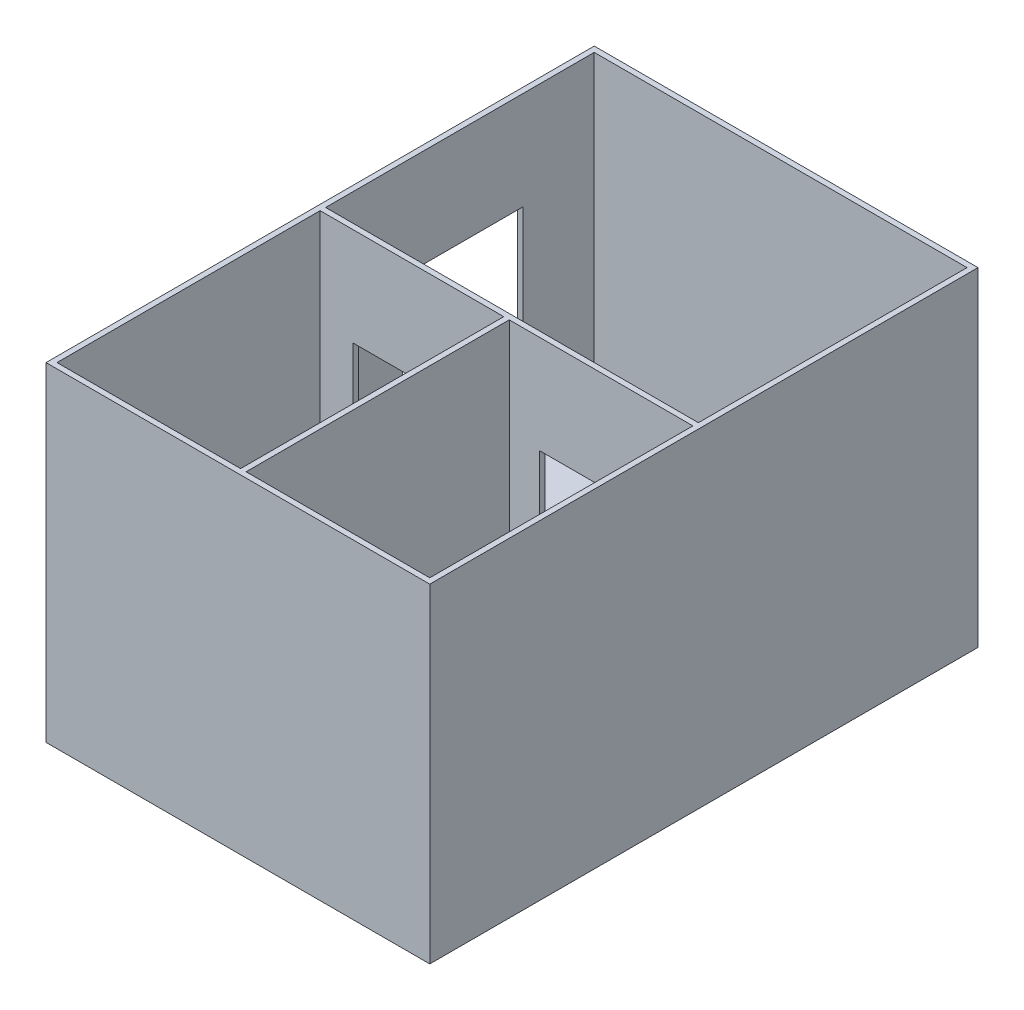
SolidWorks part; units mm, degrees
ref_plane "Front Plane" through (0, 0, 0) normal (0, 0, 1) x (1, 0, 0)
ref_plane "Top Plane" through (0, 0, 0) normal (0, 1, 0) x (1, 0, 0)
ref_plane "Right Plane" through (0, 0, 0) normal (1, 0, 0) x (0, 0, -1)
sketch "Sketch2" plane through (0, 0, 0) normal (0, 1, 0) x (1, 0, 0)
  line L1 (1750, -2500) -> (-1750, -2500)
  line L2 (1750, -2500) -> (1750, 2500)
  line L3 (1750, 2500) -> (-1750, 2500)
  line L4 (-1750, -2500) -> (-1750, 2500)
  line L5 (1750, -2500) -> (-1750, 2500) construction
  line L6 (1750, 2500) -> (-1750, -2500) construction
  point P0 (0, 0)
  dimension "D1" = 3500
  dimension "D2" = 5000
extrude "Boss-Extrude1" add sketch "Sketch2" along normal blind 3000
shell "Shell1" thickness 50
sketch "Sketch3" plane through (-1750, 0, 0) normal (-1, 0, 0) x (0, 0, 1)
  line L0 (0, 3000) -> (0, 0) construction
  line L1 (-2500, 3000) -> (2500, 3000) construction
  line L2 (-2500, 0) -> (2500, 0) construction
  line L3 (-2500, 3000) -> (-2500, 0) construction
  line L4 (-2500, 3000) -> (0, 3000)
  line L5 (-1250, 3000) -> (-1250, 0) construction
  line L7 (-700, 0) -> (-1800, 0)
  line L8 (-700, 0) -> (-700, 2105)
  line L9 (-700, 2105) -> (-1800, 2105)
  line L10 (-1800, 0) -> (-1800, 2105)
  line L11 (-700, 0) -> (-1800, 2105) construction
  line L12 (-700, 2105) -> (-1800, 0) construction
  point P12 (-1250, 1052.5)
  line M4 (-2500, 0) -> (2500, 0)
  dimension "D1" = 2500
  dimension "D2" = 1100
  dimension "D3" = 2105
  dimension "D4" = 2105
extrude "Cut-Extrude1" cut sketch "Sketch3" against normal blind 50 contours L10 L8 L9 M4
sketch "Sketch4" plane through (-1750, 0, 0) normal (-1, 0, 0) x (0, 0, 1)
  line L0 (-2500, 3000) -> (0, 3000)
  line L1 (-2500, 3000) -> (2500, 3000) construction
  line L2 (-700, 0) -> (2500, 0) construction
  line L3 (0, 3000) -> (50, 3000)
  line L4 (0, 3000) -> (0, 0)
  line L5 (0, 0) -> (50, 0)
  line L6 (50, 3000) -> (50, 0)
  line L7 (0, 3000) -> (50, 0) construction
  line L8 (0, 0) -> (50, 3000) construction
  point P8 (25, 1500)
  line M8 (-700, 0) -> (2500, 0)
  line M10 (2500, 3000) -> (-2500, 3000)
  dimension "D1" = 2500
  dimension "D2" = 50
extrude "Boss-Extrude2" add sketch "Sketch4" against normal blind 3500 contours L6 L4 M10 M8
sketch "Sketch6" plane through (0, 0, 2500) normal (0, 0, 1) x (1, 0, 0)
  line L0 (-1750, 3000) -> (1750, 3000) construction
  line L1 (-25, 3000) -> (25, 3000)
  line L2 (-25, 3000) -> (-25, 0)
  line L3 (-25, 0) -> (25, 0)
  line L4 (25, 3000) -> (25, 0)
  line L5 (-25, 3000) -> (25, 0) construction
  line L6 (-25, 0) -> (25, 3000) construction
  line L7 (-1750, 0) -> (1750, 0) construction
  line L8 (0, 0) -> (0, 3000) construction
  point P4 (0, 1500)
  point P12 (-180.4943, 1500)
  dimension "D1" = 50
extrude "Boss-Extrude3" add sketch "Sketch6" against normal blind 2500
sketch "Sketch7" plane through (0, 0, 0) normal (0, 0, -1) x (-1, 0, 0)
  line L0 (0, 3000) -> (0, 50) construction
  line L1 (300, 2105) -> (1400, 2105)
  line L2 (300, 2105) -> (300, 5)
  line L3 (300, 5) -> (1400, 5)
  line L4 (1400, 2105) -> (1400, 5)
  line L5 (300, 2105) -> (1400, 5) construction
  line L6 (300, 5) -> (1400, 2105) construction
  line L7 (-1700, 3000) -> (1700, 3000) construction
  line L8 (-1700, 50) -> (1700, 50) construction
  line L9 (0, 3000) -> (1700, 3000)
  line L10 (850, 3000) -> (850, 5) construction
  line L11 (-300, 5) -> (-1400, 5)
  line L12 (-1400, 2105) -> (-1400, 5)
  line L13 (-300, 2105) -> (-1400, 2105)
  line L14 (-300, 2105) -> (-300, 5)
  point P4 (850, 1055)
  line M7 (-1700, 50) -> (1700, 50)
  dimension "D1" = 1100
  dimension "D2" = 2100
  dimension "D3" = 2055
extrude "Cut-Extrude5" cut sketch "Sketch7" against normal blind 50 contours L4 L1 L2 M7 | L4 L2 L3 M7 | L11 L12 L13 L14
